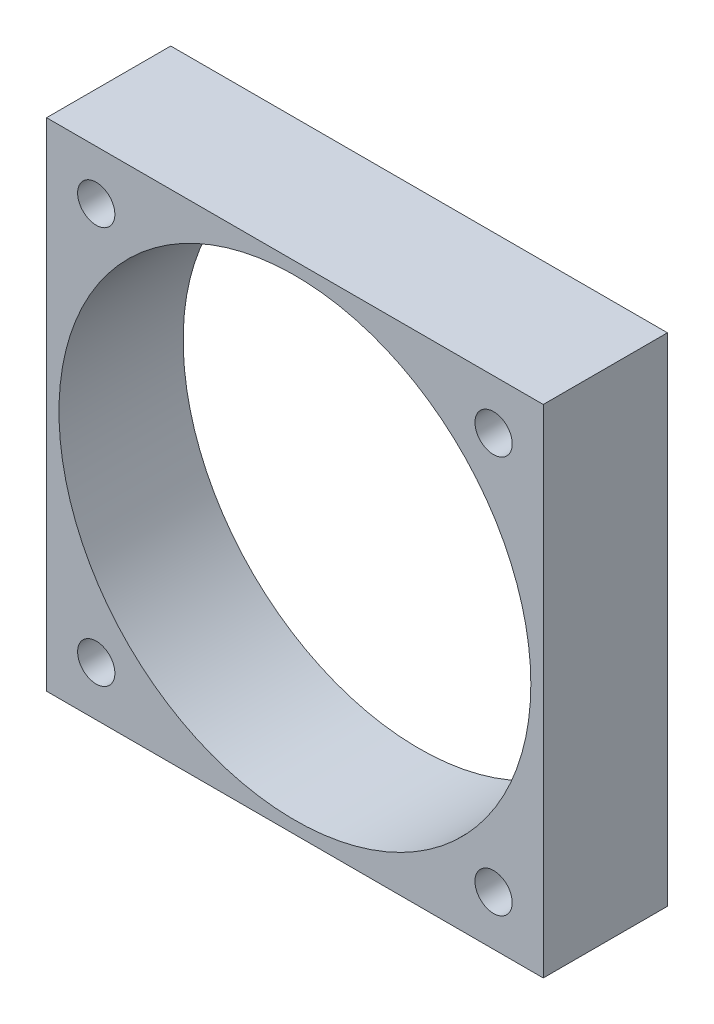
SolidWorks part; units mm, degrees
ref_plane "前基準面" through (0, 0, 0) normal (0, 0, 1) x (1, 0, 0)
ref_plane "上基準面" through (0, 0, 0) normal (0, 1, 0) x (1, 0, 0)
ref_plane "右基準面" through (0, 0, 0) normal (1, 0, 0) x (0, 0, -1)
sketch "草圖1" plane through (0, 0, 0) normal (0, 0, 1) x (1, 0, 0)
  line L1 (-20, 20) -> (20, 20)
  line L2 (-20, 20) -> (-20, -20)
  line L3 (-20, -20) -> (20, -20)
  line L4 (20, 20) -> (20, -20)
  point P4 (0, 20)
  point P6 (-20, 0)
  dimension "D1" = 40
  dimension "D2" = 40
extrude "填料-伸長1" add sketch "草圖1" along normal blind 10
sketch "草圖2" plane through (0, 0, 10) normal (0, 0, 1) x (1, 0, 0)
  circle A0 centre (0, 0) radius 19
  dimension "D1" = 38
extrude "除料-伸長1" cut sketch "草圖2" against normal through all
sketch "草圖3" plane through (0, 0, 10) normal (0, 0, 1) x (1, 0, 0)
  circle A0 centre (-16, 16) radius 1.5
  circle A1 centre (-16, -16) radius 1.5
  circle A2 centre (16, -16) radius 1.5
  circle A3 centre (16, 16) radius 1.5
  point P11 (0, 0)
  dimension "D9" = 3
  dimension "D10" = 3
  dimension "D11" = 3
  dimension "D12" = 3
  dimension "D1" = 32
  dimension "D2" = 32
  dimension "D3" = 16
  dimension "D4" = 32
  dimension "D5" = 16
  dimension "D6" = 16
  dimension "D7" = 16
  dimension "D8" = 32
extrude "除料-伸長2" cut sketch "草圖3" against normal through all
